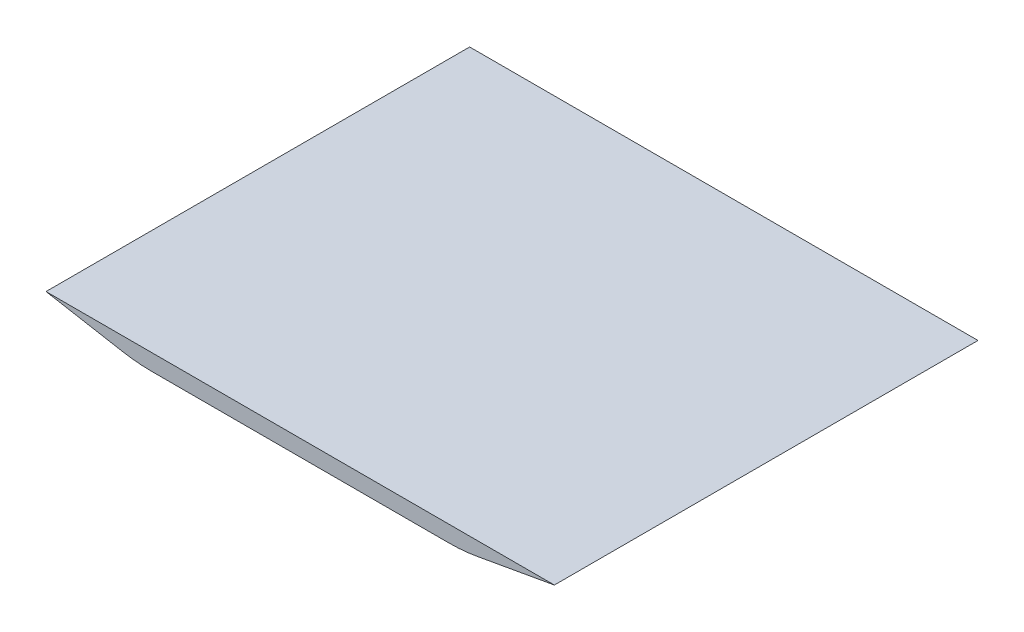
SolidWorks part; units mm, degrees
ref_plane "Front Plane" through (0, 0, 0) normal (0, 0, 1) x (1, 0, 0)
ref_plane "Top Plane" through (0, 0, 0) normal (0, 1, 0) x (1, 0, 0)
ref_plane "Right Plane" through (0, 0, 0) normal (1, 0, 0) x (0, 0, -1)
sketch "Sketch1" plane through (0, 0, 0) normal (0, 0, 1) x (1, 0, 0)
  line L0 (0, 0) -> (156, 0)
  line L1 (156, 0) -> (128, -5)
  line L2 (128, -5) -> (28, -5)
  line L3 (28, -5) -> (0, 0)
  dimension "D1" = 100
  dimension "D2" = 5
  dimension "D3" = 28
  dimension "D4" = 28
extrude "Boss-Extrude1" add sketch "Sketch1" along normal blind 130
fillet "Fillet1" radius 50 2 edges at (128, -5, 65) (28, -5, 65)
